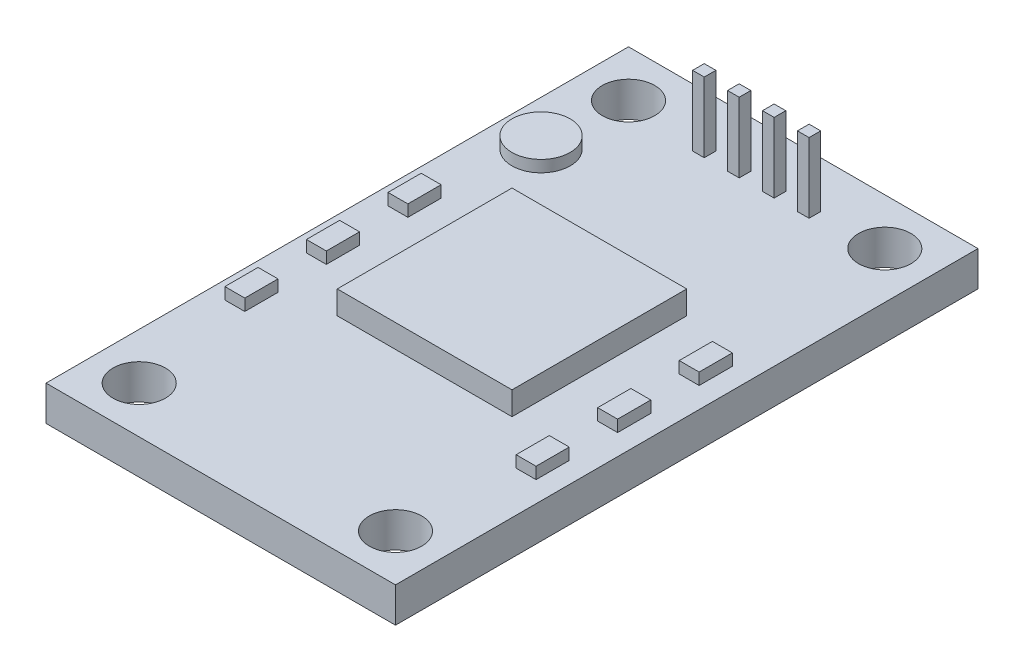
SolidWorks part; units mm, degrees
ref_plane "Front Plane" through (0, 0, 0) normal (0, 0, 1) x (1, 0, 0)
ref_plane "Top Plane" through (0, 0, 0) normal (0, 1, 0) x (1, 0, 0)
ref_plane "Right Plane" through (0, 0, 0) normal (1, 0, 0) x (0, 0, -1)
sketch "Sketch1" plane through (0, 0, 0) normal (0, 1, 0) x (1, 0, 0)
  line L1 (-15, -25) -> (15, -25)
  line L2 (-15, -25) -> (-15, 25)
  line L3 (-15, 25) -> (15, 25)
  line L4 (15, -25) -> (15, 25)
  line L5 (-15, -25) -> (15, 25) construction
  line L6 (-15, 25) -> (15, -25) construction
  point P0 (0, 0)
  dimension "D1" = 50
  dimension "D2" = 30
extrude "Boss-Extrude1" add sketch "Sketch1" along normal blind 3
sketch "Sketch2" plane through (0, 3, 0) normal (0, 1, 0) x (1, 0, 0)
  line L0 (-15, 25) -> (-15, -25) construction
  line L1 (15, 25) -> (-15, 25) construction
  circle A0 centre (-11, 21) radius 2.25
  dimension "D1" = 4.5
  dimension "D2" = 4
  dimension "D3" = 4
extrude "Cut-Extrude1" cut sketch "Sketch2" against normal blind 3
pattern_linear "LPattern1" count 2 spacing 22 along (1, 0, 0) count 2 spacing 42 along (0, 0, 1) of "Cut-Extrude1"
sketch "Sketch3" plane through (0, 3, 0) normal (0, 1, 0) x (1, 0, 0)
  line L0 (15, 25) -> (-15, 25) construction
  line L1 (-4.5, 21) -> (-3.5, 21)
  line L2 (-4.5, 21) -> (-4.5, 20)
  line L3 (-4.5, 20) -> (-3.5, 20)
  line L4 (-3.5, 21) -> (-3.5, 20)
  line L5 (-4.5, 21) -> (-3.5, 20) construction
  line L6 (-4.5, 20) -> (-3.5, 21) construction
  line L7 (-15, 25) -> (-15, -25) construction
  point P0 (-4, 20.5)
  dimension "D1" = 1
  dimension "D2" = 1
  dimension "D3" = 4
  dimension "D4" = 11
extrude "Boss-Extrude2" add sketch "Sketch3" along normal blind 6
pattern_linear "LPattern2" count 4 spacing 3 along (1, 0, 0) of "Boss-Extrude2"
sketch "Sketch4" plane through (0, 3, 0) normal (0, 1, 0) x (1, 0, 0)
  line L1 (-7.5, 7.5) -> (7.5, 7.5)
  line L2 (-7.5, 7.5) -> (-7.5, -7.5)
  line L3 (-7.5, -7.5) -> (7.5, -7.5)
  line L4 (7.5, 7.5) -> (7.5, -7.5)
  line L5 (-7.5, 7.5) -> (7.5, -7.5) construction
  line L6 (-7.5, -7.5) -> (7.5, 7.5) construction
  point P0 (0, 0)
  dimension "D1" = 15
  dimension "D2" = 15
extrude "Boss-Extrude3" add sketch "Sketch4" along normal blind 2
sketch "Sketch5" plane through (0, 3, 0) normal (0, 1, 0) x (1, 0, 0)
  line L1 (-13.4985, -8.2986) -> (-11.7889, -8.2986)
  line L2 (-13.4985, -8.2986) -> (-13.4985, -11.1478)
  line L3 (-13.4985, -11.1478) -> (-11.7889, -11.1478)
  line L4 (-11.7889, -8.2986) -> (-11.7889, -11.1478)
  line L5 (-13.4985, -8.2986) -> (-11.7889, -11.1478) construction
  line L6 (-13.4985, -11.1478) -> (-11.7889, -8.2986) construction
  point P0 (-12.6437, -9.7232)
extrude "Boss-Extrude4" add sketch "Sketch5" along normal blind 1
pattern_linear "LPattern3" count 3 spacing 7 along (0, 0, -1) count 2 spacing 25 along (1, 0, 0) of "Boss-Extrude4"
sketch "Sketch6" plane through (0, 3, 0) normal (0, 1, 0) x (1, 0, 0)
  circle A0 centre (-11.1478, 13.641) radius 2.5
  dimension "D1" = 5
extrude "Boss-Extrude5" add sketch "Sketch6" along normal blind 1
